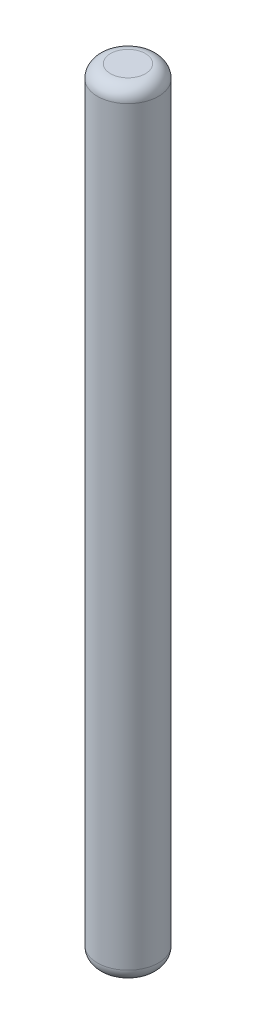
SolidWorks part; units mm, degrees
ref_plane "정면" through (0, 0, 0) normal (0, 0, 1) x (1, 0, 0)
ref_plane "윗면" through (0, 0, 0) normal (0, 1, 0) x (1, 0, 0)
ref_plane "우측면" through (0, 0, 0) normal (1, 0, 0) x (0, 0, -1)
sketch "스케치1" plane through (0, 0, 0) normal (0, 1, 0) x (1, 0, 0)
  circle A0 centre (0, 0) radius 0.35
  dimension "D1" = 0.7
extrude "보스-돌출1" add sketch "스케치1" along normal blind 8.9
fillet "필렛1" radius 0.15 2 edges at (0, 0, 0.35) (0, 8.9, 0.35)
